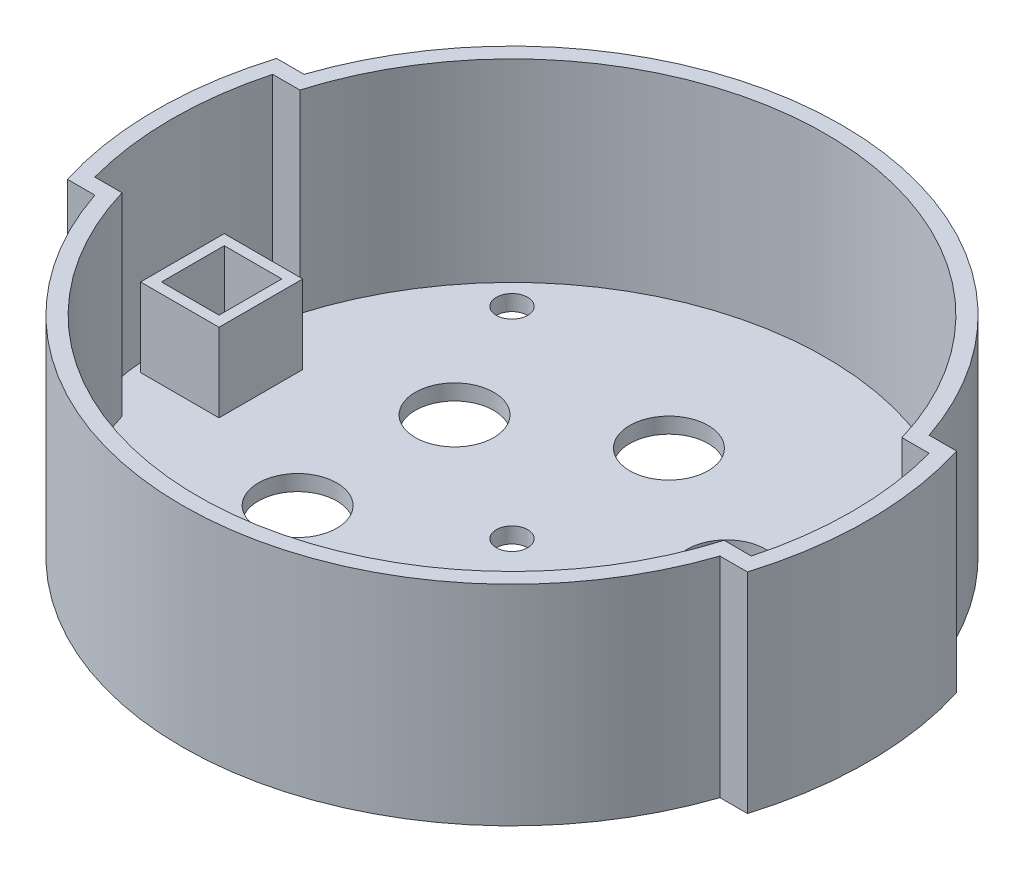
SolidWorks part; units mm, degrees
ref_plane "Front Plane" through (0, 0, 0) normal (0, 0, 1) x (1, 0, 0)
ref_plane "Top Plane" through (0, 0, 0) normal (0, 1, 0) x (1, 0, 0)
ref_plane "Right Plane" through (0, 0, 0) normal (1, 0, 0) x (0, 0, -1)
sketch "Sketch1" plane through (0, 0, 0) normal (0, 1, 0) x (1, 0, 0)
  circle A0 centre (0, 0) radius 68
  dimension "D1" = 136
extrude "Boss-Extrude1" add sketch "Sketch1" along normal blind 40
sketch "Sketch2" plane through (0, 40, 0) normal (0, 1, 0) x (1, 0, 0)
  line L1 (0, 37.0764) -> (0, -27.4787) construction
  line L5 (-59.7411, -20) -> (-64.9923, -20)
  line L6 (-59.7411, 20) -> (-64.9923, 20)
  line L7 (59.7411, -20) -> (64.9923, -20)
  line L8 (59.7411, 20) -> (64.9923, 20)
  line L9 (-28.4675, 0) -> (19.3594, 0) construction
  arc A0 (-59.7411, -20) -> (59.7411, -20) centre (0, 0) ccw
  arc A1 (-64.9923, -20) -> (64.9923, -20) centre (0, 0) ccw
  circle A2 centre (0, 0) radius 68 construction
  arc A3 (59.7411, 20) -> (-59.7411, 20) centre (0, 0) ccw
  arc A4 (64.9923, 20) -> (-64.9923, 20) centre (0, 0) ccw
  dimension "D1" = 126
  dimension "D2" = 40
  dimension "D3" = 40
extrude "Cut-Extrude1" cut sketch "Sketch2" against normal up to surface (40 mm away) up to face at (0, 0, 68)
shell "Shell1" thickness 3
sketch "Sketch3" plane through (0, 0, 0) normal (0, -1, 0) x (1, 0, 0)
  line L0 (-78.2757, 0) -> (93.912, 0) construction
  line L1 (0, -51.8142) -> (0, 50.9292) construction
  line L2 (-7.0646, -7.0646) -> (9.5136, 9.5136) construction
  circle A0 centre (-38.4666, 38.4666) radius 3
  circle A1 centre (38.4666, -38.4666) radius 3
  circle A2 centre (0, 30) radius 7.5
  circle A3 centre (25.9808, 15) radius 7.5
  circle A4 centre (25.9808, -15) radius 7.5
  circle A5 centre (0, -30) radius 7.5
  circle A6 centre (-25.9808, -15) radius 7.5
  circle A7 centre (-25.9808, 15) radius 7.5
  circle A8 centre (-38.4666, -38.4666) radius 3
  circle A9 centre (38.4666, 38.4666) radius 3
  point P24 (0, 0)
  point P26 (0, 0)
  point P27 (0, 0)
  point P28 (38.4666, -38.4666)
  point P29 (0, 0)
  point P30 (-40.3969, 36.4342)
  dimension "D1" = 6
  dimension "D2" = 6
  dimension "D5" = 15
  dimension "D9" = 6
  dimension "D10" = 6
  dimension "D3" = 54.4
  dimension "D4" = 54.4
  dimension "D6" = 30
  dimension "D8" = 30
  dimension "D11" = 54.4
  dimension "D12" = 54.4
  dimension "D13" = 45
  dimension "D7" = 6
extrude "Cut-Extrude2" cut sketch "Sketch3" against normal through all both and the other way through all
sketch "Sketch4" plane through (0, 3, 0) normal (0, 1, 0) x (1, 0, 0)
  circle A0 centre (0, 0) radius 3
  dimension "D1" = 6
extrude "Cut-Extrude3" cut sketch "Sketch4" against normal up to surface (3 mm away) up to face at (-38.4666, 0, -35.4666)
sketch "Sketch6" plane through (0, 3, 0) normal (0, 1, 0) x (1, 0, 0)
  line L0 (0, 0) -> (-13.2822, 0) construction
  line L1 (-61, 6) -> (-50, 6)
  line L2 (-61, 6) -> (-61, -6)
  line L3 (-61, -6) -> (-50, -6)
  line L4 (-50, 6) -> (-50, -6)
  line L6 (-63, -8) -> (-48, -8)
  line L7 (-63, -8) -> (-63, 8)
  line L8 (-63, 8) -> (-48, 8)
  line L9 (-48, -8) -> (-48, 8)
  point P7 (-50, 0)
  dimension "D1" = 11
  dimension "D2" = 12
  dimension "D3" = 50
  dimension "D4" = 2
  dimension "D5" = 2
  dimension "D6" = 2
  dimension "D7" = 2
extrude "Boss-Extrude2" add sketch "Sketch6" along normal blind 15
sketch "Sketch7" plane through (0, 3, 0) normal (0, 1, 0) x (1, 0, 0)
  line L0 (-61, -6) -> (-50, -6) construction
  line L1 (-57.5, -6) -> (-53.5, -6)
  line L2 (-57.5, -6) -> (-57.5, -3.5)
  line L3 (-57.5, -3.5) -> (-53.5, -3.5)
  line L4 (-53.5, -6) -> (-53.5, -3.5)
  line L5 (-63, -8) -> (-48, -8) construction
  point P8 (-55.5, -8)
  point P9 (-55.5, -3.5)
  dimension "D1" = 4
  dimension "D2" = 2.5
extrude "Cut-Extrude5" cut sketch "Sketch7" against normal up to surface (3 mm away) up to face at (0, 0, 3)
